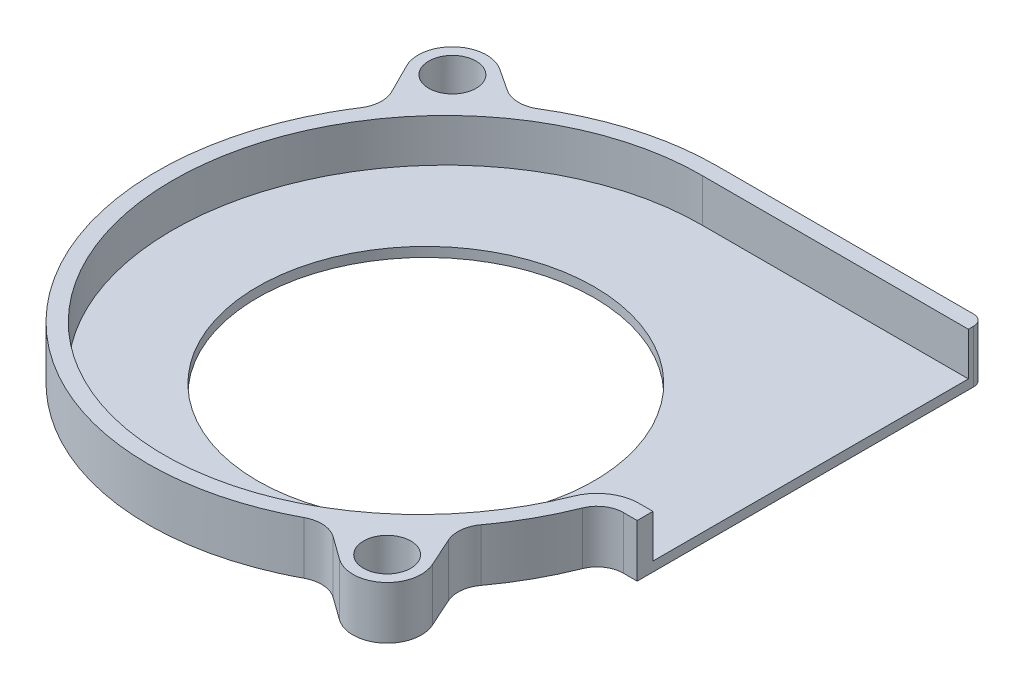
SolidWorks part; units mm, degrees
ref_plane "Front Plane" through (0, 0, 0) normal (0, 0, 1) x (1, 0, 0)
ref_plane "Top Plane" through (0, 0, 0) normal (0, 1, 0) x (1, 0, 0)
ref_plane "Right Plane" through (0, 0, 0) normal (1, 0, 0) x (0, 0, -1)
sketch "Sketch19" plane through (101.6679, 0, -9.2414) normal (0, 1, 0) x (-1, 0, 0)
  line L180 (73.5095, 9.2414) -> (95.2051, 9.2414)
  line L186 (79.9167, 11.9238) -> (79.5136, 11.896)
  line L187 (82.3906, 14.2171) -> (82.2795, 13.8418)
  line L188 (79.5136, 11.896) -> (76.2336, 11.896)
  line L189 (108.1308, 9.2414) -> (129.8264, 9.2414)
  line L190 (99.5137, 9.2414) -> (103.8222, 9.2414)
  line L191 (101.6679, 8.6855) -> (101.6679, 12.994)
  line L192 (101.6679, -18.9032) -> (101.6679, 4.3769)
  line L193 (88.3531, 30.395) -> (88.3531, 32.4937)
  line L194 (88.3531, 29.1024) -> (88.3531, 29.7557)
  line L195 (88.3531, 26.3644) -> (88.3531, 28.4631)
  line L196 (89.326, 29.4221) -> (91.4108, 29.4221)
  line L197 (88.0335, 29.4221) -> (88.6728, 29.4221)
  line L198 (85.2954, 29.4221) -> (87.3802, 29.4221)
  line L199 (117.3872, -12.6488) -> (117.3872, -10.5501)
  line L200 (117.3872, -13.9414) -> (117.3872, -13.2882)
  line L201 (117.3872, -16.6794) -> (117.3872, -14.5807)
  line L202 (118.3462, -13.6217) -> (120.4449, -13.6217)
  line L203 (117.0536, -13.6217) -> (117.7069, -13.6217)
  line L204 (114.3156, -13.6217) -> (116.4143, -13.6217)
  line L205 (100.3893, 23.6264) -> (100.3198, 24.2935)
  line L206 (98.8882, 23.4179) -> (98.7492, 24.0712)
  line L207 (97.4289, 23.0427) -> (97.2204, 23.682)
  line L208 (96.0112, 22.5284) -> (95.7333, 23.14)
  line L209 (94.6492, 21.8613) -> (94.3156, 22.445)
  line L210 (93.3705, 21.0552) -> (92.9674, 21.5972)
  line L211 (92.1752, 20.124) -> (91.7305, 20.6243)
  line L212 (91.0911, 19.0677) -> (90.5908, 19.5263)
  line L213 (90.1182, 17.9141) -> (89.5762, 18.3033)
  line L214 (89.2843, 16.6632) -> (88.7006, 16.9968)
  line L215 (88.5755, 15.329) -> (87.964, 15.593)
  line L216 (88.0057, 13.9252) -> (87.3802, 14.1337)
  line L217 (87.6026, 12.4659) -> (86.9494, 12.6049)
  line L218 (87.3385, 10.9787) -> (86.6714, 11.0482)
  line L219 (87.2412, 9.4777) -> (86.5602, 9.4777)
  line L220 (87.2968, 7.9627) -> (86.6297, 7.8932)
  line L221 (87.5053, 6.4617) -> (86.8521, 6.3227)
  line L222 (87.8667, 5.0023) -> (87.2412, 4.7939)
  line L223 (88.3948, 3.5847) -> (87.7833, 3.3067)
  line L224 (89.0619, 2.2226) -> (88.4782, 1.8891)
  line L225 (89.8542, 0.944) -> (89.3121, 0.5548)
  line L226 (90.7854, -0.2374) -> (90.2989, -0.6961)
  line L227 (91.8417, -1.3215) -> (91.3969, -1.8219)
  line L228 (93.0091, -2.2944) -> (92.6061, -2.8364)
  line L229 (94.26, -3.1422) -> (93.9264, -3.726)
  line L230 (95.5943, -3.851) -> (95.3163, -4.4626)
  line L231 (96.998, -4.407) -> (96.7895, -5.0463)
  line L232 (98.4435, -4.8239) -> (98.3045, -5.4772)
  line L233 (99.9306, -5.088) -> (99.8611, -5.7551)
  line L234 (101.4456, -5.1853) -> (101.4456, -5.8524)
  line L235 (102.9605, -5.1297) -> (103.03, -5.7968)
  line L236 (104.4476, -4.9212) -> (104.5866, -5.5745)
  line L237 (105.9209, -4.546) -> (106.1294, -5.1853)
  line L238 (107.3385, -4.0317) -> (107.6026, -4.6433)
  line L239 (108.6867, -3.3646) -> (109.0203, -3.9483)
  line L240 (109.9654, -2.5585) -> (110.3684, -3.1005)
  line L241 (111.1606, -1.6273) -> (111.6054, -2.1276)
  line L242 (112.2447, -0.571) -> (112.7451, -1.0296)
  line L243 (113.2176, 0.5826) -> (113.7597, 0.1934)
  line L244 (114.0515, 1.8335) -> (114.6353, 1.4999)
  line L245 (114.7604, 3.1677) -> (115.3719, 2.9037)
  line L246 (115.3302, 4.5715) -> (115.9696, 4.363)
  line L247 (115.7472, 6.0308) -> (116.4004, 5.8918)
  line L248 (115.9973, 7.518) -> (116.6645, 7.4485)
  line L249 (116.1085, 9.019) -> (116.7757, 9.019)
  line L250 (116.0529, 10.534) -> (116.7201, 10.6035)
  line L251 (115.8306, 12.0211) -> (116.4977, 12.174)
  line L252 (115.4692, 13.4944) -> (116.1085, 13.7028)
  line L253 (114.955, 14.912) -> (115.5665, 15.19)
  line L254 (114.2878, 16.2741) -> (114.8577, 16.6076)
  line L255 (113.4817, 17.5527) -> (114.0238, 17.9419)
  line L256 (112.5505, 18.7341) -> (113.0509, 19.1789)
  line L257 (111.4942, 19.8182) -> (111.939, 20.3185)
  line L258 (110.3406, 20.7911) -> (110.7298, 21.3331)
  line L259 (109.0759, 21.6389) -> (109.4233, 22.2088)
  line L260 (107.7416, 22.3477) -> (108.0196, 22.9593)
  line L261 (106.3517, 22.9037) -> (106.5463, 23.543)
  line L262 (104.8924, 23.3206) -> (105.0314, 23.9739)
  line L263 (103.4053, 23.5847) -> (103.4747, 24.2379)
  line L264 (101.8903, 23.682) -> (101.8903, 24.3491)
  line L265 (116.7479, 10.1587) -> (116.7757, 9.2414)
  line L266 (116.6645, 11.0621) -> (116.7479, 10.1587)
  line L267 (116.5255, 11.9655) -> (116.6645, 11.0621)
  line L268 (100.7645, 24.3213) -> (101.6679, 24.3491)
  line L269 (99.8472, 24.2379) -> (100.7645, 24.3213)
  line L270 (86.588, 10.1587) -> (86.6714, 11.0621)
  line L271 (86.5602, 9.2414) -> (86.588, 10.1587)
  line L272 (86.588, 8.338) -> (86.5602, 9.2414)
  line L273 (86.6714, 7.4207) -> (86.588, 8.338)
  line L274 (101.6679, -5.8524) -> (100.7645, -5.8246)
  line L275 (102.5852, -5.8246) -> (101.6679, -5.8524)
  line L276 (116.6645, 7.4207) -> (116.5255, 6.5312)
  line L277 (116.7479, 8.338) -> (116.6645, 7.4207)
  line L278 (116.7757, 9.2414) -> (116.7479, 8.338)
  line L279 (116.0807, 10.117) -> (116.1085, 9.2414)
  line L280 (115.9973, 10.9926) -> (116.0807, 10.117)
  line L281 (115.8723, 11.8543) -> (115.9973, 10.9926)
  line L282 (100.7923, 23.6542) -> (101.6679, 23.682)
  line L283 (99.9306, 23.5708) -> (100.7923, 23.6542)
  line L284 (87.2551, 10.117) -> (87.3385, 10.9926)
  line L285 (87.2273, 9.2414) -> (87.2551, 10.117)
  line L286 (87.2551, 8.3797) -> (87.2273, 9.2414)
  line L287 (87.3385, 7.5041) -> (87.2551, 8.3797)
  line L288 (101.6679, -5.1853) -> (100.7923, -5.1575)
  line L289 (102.5435, -5.1575) -> (101.6679, -5.1853)
  line L290 (115.9973, 7.5041) -> (115.8723, 6.6424)
  line L291 (116.0807, 8.3797) -> (115.9973, 7.5041)
  line L292 (116.1085, 9.2414) -> (116.0807, 8.3797)
  line L293 (111.9668, 9.978) -> (111.9946, 9.2414)
  line L294 (111.8834, 10.7146) -> (111.9668, 9.978)
  line L295 (111.7583, 11.4374) -> (111.8834, 10.7146)
  line L296 (100.9313, 19.5402) -> (101.6679, 19.568)
  line L297 (100.1947, 19.4707) -> (100.9313, 19.5402)
  line L298 (91.3691, 9.978) -> (91.4525, 10.7146)
  line L299 (91.3413, 9.2414) -> (91.3691, 9.978)
  line L300 (91.3691, 8.5048) -> (91.3413, 9.2414)
  line L301 (91.4525, 7.7821) -> (91.3691, 8.5048)
  line L302 (101.6679, -1.0713) -> (100.9313, -1.0435)
  line L303 (102.4046, -1.0435) -> (101.6679, -1.0713)
  line L304 (111.8834, 7.7821) -> (111.7583, 7.0593)
  line L305 (111.9668, 8.5048) -> (111.8834, 7.7821)
  line L306 (111.9946, 9.2414) -> (111.9668, 8.5048)
  line L307 (98.6797, 31.9099) -> (105.8375, 32.2852)
  line L308 (100.5838, 31.4096) -> (100.5561, 32.0211)
  line L309 (103.989, 31.6737) -> (103.9612, 32.1879)
  line L310 (105.8375, 32.2852) -> (105.8792, 31.5903)
  line L311 (98.7214, 31.0482) -> (98.6797, 31.9099)
  line L312 (86.2961, 22.8481) -> (86.9494, 23.682)
  line L313 (82.3906, 14.2171) -> (82.6269, 15.2595)
  line L314 (87.1856, 24.0156) -> (86.9494, 23.682)
  line L315 (86.7131, 27.7265) -> (86.9911, 27.4207)
  line L316 (90.6325, 30.2838) -> (90.3962, 30.6174)
  line L317 (94.2739, 29.436) -> (93.8986, 29.297)
  line L318 (90.1877, 30.9231) -> (90.3962, 30.6174)
  line L319 (86.7131, 27.7265) -> (86.4768, 27.9906)
  line L320 (90.1043, 29.7418) -> (90.1321, 29.4221)
  line L321 (90.0209, 30.0336) -> (90.1043, 29.7418)
  line L322 (86.588, 29.4221) -> (86.6158, 29.7418)
  line L323 (86.6158, 29.1163) -> (86.588, 29.4221)
  line L324 (90.1043, 29.1163) -> (90.0209, 28.8245)
  line L325 (90.1321, 29.4221) -> (90.1043, 29.1163)
  line L326 (115.2051, -14.678) -> (115.4414, -14.9699)
  line L327 (111.7166, -13.997) -> (112.0641, -13.858)
  line L328 (120.153, -7.4091) -> (119.3747, -8.2986)
  line L329 (125.6429, 4.1545) -> (125.3928, 3.0009)
  line L330 (119.1384, -8.5904) -> (119.3747, -8.2986)
  line L331 (119.2357, -12.1485) -> (119.0272, -11.8427)
  line L332 (115.6777, -15.2618) -> (115.4414, -14.9699)
  line L333 (119.2357, -12.1485) -> (119.4442, -12.4681)
  line L334 (119.1245, -13.316) -> (119.1523, -13.6217)
  line L335 (119.0411, -13.0102) -> (119.1245, -13.316)
  line L336 (115.6082, -13.6217) -> (115.636, -13.316)
  line L337 (115.636, -13.9275) -> (115.6082, -13.6217)
  line L338 (119.1245, -13.9275) -> (119.0411, -14.2194)
  line L339 (119.1523, -13.6217) -> (119.1245, -13.9275)
  line L340 (82.9466, 18.4283) -> (81.6262, 13.3137)
  line L341 (82.9883, 16.4825) -> (82.474, 16.6076)
  line L342 (82.5713, 15.0093) -> (82.0988, 15.1344)
  line L343 (81.6262, 13.3137) -> (81.9737, 13.2303)
  line L344 (83.6554, 18.2477) -> (82.9466, 18.4283)
  line L345 (126.6992, 13.411) -> (126.6992, 6.2393)
  line L346 (126.1294, 11.5347) -> (126.6992, 11.5347)
  line L347 (126.1711, 8.1156) -> (126.6992, 8.1156)
  line L348 (126.6992, 6.2393) -> (125.9904, 6.2393)
  line L349 (125.907, 13.411) -> (126.6992, 13.411)
  line L350 (90.7715, -16.5126) -> (83.5998, -16.5126)
  line L351 (88.8952, -16.0262) -> (88.8952, -16.5126)
  line L352 (85.49, -16.0262) -> (85.49, -16.5126)
  line L353 (83.5998, -16.5126) -> (83.5998, -16.0262)
  line L354 (90.7715, -16.0262) -> (90.7715, -16.5126)
  line L355 (119.7222, 25.8224) -> (120.5422, 25.0441)
  line L356 (94.2739, 29.436) -> (95.3163, 29.9086)
  line L357 (76.2336, -15.2479) -> (76.2336, 11.896)
  line L358 (76.2614, -15.4424) -> (76.2336, -15.2479)
  line L359 (76.3309, -15.637) -> (76.2614, -15.4424)
  line L360 (76.456, -15.8038) -> (76.3309, -15.637)
  line L361 (76.6227, -15.9289) -> (76.456, -15.8038)
  line L362 (76.8173, -15.9984) -> (76.6227, -15.9289)
  line L363 (77.0119, -16.0262) -> (76.8173, -15.9984)
  line L364 (103.7666, -16.0262) -> (77.0119, -16.0262)
  line L365 (104.6283, -15.9984) -> (103.7666, -16.0262)
  line L366 (105.49, -15.9289) -> (104.6283, -15.9984)
  line L367 (110.7854, -14.4278) -> (109.8264, -14.817)
  line L368 (111.7166, -13.997) -> (110.7854, -14.4278)
  line L369 (125.8514, 5.2664) -> (125.6429, 4.1545)
  line L370 (120.5422, 25.0441) -> (121.1676, 24.3908)
  spline S28 degree 3 poles (82.2795, 13.8418) (82.1213, 13.5208) (81.8076, 12.8842) (80.9543, 12.1818) (80.2645, 12.0103) (79.9167, 11.9238) knots 0 0 0 0 0.335193 0.664797 1 1 1 1
  spline S29 degree 3 poles (101.6679, 24.3491) (104.0069, 24.0252) (108.6295, 23.3848) (114.3269, 18.6424) (115.7868, 14.2088) (116.5255, 11.9655) knots 0 0 0 0 0.335972 0.664018 1 1 1 1
  spline S30 degree 3 poles (86.6714, 11.0621) (87.2366, 13.2458) (88.355, 17.5661) (93.3409, 22.5601) (97.6629, 23.6747) (99.8472, 24.2379) knots 0 0 0 0 0.335761 0.664295 1 1 1 1
  spline S31 degree 3 poles (100.7645, -5.8246) (98.4503, -5.3637) (93.8723, -4.4518) (88.48, 0.6318) (87.2787, 5.141) (86.6714, 7.4207) knots 0 0 0 0 0.335739 0.664168 1 1 1 1
  spline S32 degree 3 poles (116.5255, 6.5312) (115.8334, 4.3849) (114.4633, 0.1363) (109.1811, -4.5461) (104.7988, -5.3956) (102.5852, -5.8246) knots 0 0 0 0 0.335641 0.664413 1 1 1 1
  spline S33 degree 3 poles (101.6679, 23.682) (103.9054, 23.3721) (108.3203, 22.7605) (113.7584, 18.2278) (115.1613, 13.998) (115.8723, 11.8543) knots 0 0 0 0 0.336336 0.663662 1 1 1 1
  spline S34 degree 3 poles (87.3385, 10.9926) (87.8783, 13.0779) (88.947, 17.2069) (93.7146, 21.9749) (97.8452, 23.0354) (99.9306, 23.5708) knots 0 0 0 0 0.335633 0.664571 1 1 1 1
  spline S35 degree 3 poles (100.7923, -5.1575) (98.5828, -4.7133) (94.2132, -3.8348) (89.057, 1.0146) (87.9157, 5.3244) (87.3385, 7.5041) knots 0 0 0 0 0.335787 0.664078 1 1 1 1
  spline S36 degree 3 poles (115.8723, 6.6424) (115.2066, 4.5932) (113.8893, 0.5378) (108.8443, -3.9341) (104.6584, -4.7469) (102.5435, -5.1575) knots 0 0 0 0 0.335708 0.664385 1 1 1 1
  spline S37 degree 3 poles (101.6679, 19.568) (103.228, 19.3569) (106.3141, 18.9394) (110.1593, 15.8464) (111.2213, 12.9179) (111.7583, 11.4374) knots 0 0 0 0 0.335769 0.664184 1 1 1 1
  spline S38 degree 3 poles (91.4525, 10.7146) (91.8473, 12.1526) (92.6277, 14.9948) (95.9245, 18.2679) (98.7596, 19.0665) (100.1947, 19.4707) knots 0 0 0 0 0.335838 0.663808 1 1 1 1
  spline S39 degree 3 poles (100.9313, -1.0435) (99.3926, -0.723) (96.3435, -0.0878) (92.7284, 3.2707) (91.8804, 6.2689) (91.4525, 7.7821) knots 0 0 0 0 0.335364 0.664577 1 1 1 1
  spline S40 degree 3 poles (111.7583, 7.0593) (111.2607, 5.6562) (110.2741, 2.8742) (106.7592, -0.1744) (103.8644, -0.7521) (102.4046, -1.0435) knots 0 0 0 0 0.3353 0.664782 1 1 1 1
  spline S41 degree 3 poles (82.6269, 15.2595) (82.9027, 16.1601) (83.4547, 17.963) (84.6972, 20.5167) (85.7635, 22.0714) (86.2961, 22.8481) knots 0 0 0 0 0.333132 0.666848 1 1 1 1
  spline S42 degree 3 poles (86.9911, 27.4207) (87.1995, 27.074) (87.6163, 26.3808) (87.7039, 25.1152) (87.3583, 24.382) (87.1856, 24.0156) knots 0 0 0 0 0.333613 0.667008 1 1 1 1
  spline S43 degree 3 poles (93.8986, 29.297) (93.5019, 29.2146) (92.707, 29.0495) (91.4909, 29.4223) (90.9183, 29.9969) (90.6325, 30.2838) knots 0 0 0 0 0.332897 0.666933 1 1 1 1
  spline S44 degree 3 poles (86.4768, 27.9906) (86.1885, 28.8219) (85.6369, 30.4125) (88.0271, 32.3046) (89.4462, 31.3972) (90.1877, 30.9231) knots 0 0 0 0 0.343302 0.656868 1 1 1 1
  spline S45 degree 3 poles (86.6158, 29.7418) (86.8446, 30.2312) (87.2875, 31.1785) (89.1095, 31.3307) (89.7103, 30.4757) (90.0209, 30.0336) knots 0 0 0 0 0.340481 0.658978 1 1 1 1
  spline S46 degree 3 poles (90.0209, 28.8245) (89.7109, 28.3825) (89.1105, 27.5268) (87.2866, 27.6775) (86.8442, 28.6264) (86.6158, 29.1163) knots 0 0 0 0 0.340673 0.659593 1 1 1 1
  spline S47 degree 3 poles (112.0641, -13.858) (112.441, -13.7794) (113.1871, -13.6238) (114.3407, -13.9227) (114.915, -14.4245) (115.2051, -14.678) knots 0 0 0 0 0.335636 0.664286 1 1 1 1
  spline S48 degree 3 poles (125.3928, 3.0009) (125.0296, 1.749) (124.3006, -0.7644) (122.5332, -4.2934) (120.9444, -6.3732) (120.153, -7.4091) knots 0 0 0 0 0.332521 0.667547 1 1 1 1
  spline S49 degree 3 poles (119.0272, -11.8427) (118.8653, -11.4887) (118.5486, -10.7962) (118.5971, -9.6046) (118.9553, -8.9336) (119.1384, -8.5904) knots 0 0 0 0 0.338158 0.661533 1 1 1 1
  spline S50 degree 3 poles (119.4442, -12.4681) (119.6189, -13.254) (119.9552, -14.7658) (117.7357, -16.4106) (116.3823, -15.6551) (115.6777, -15.2618) knots 0 0 0 0 0.341627 0.657242 1 1 1 1
  spline S51 degree 3 poles (115.636, -13.316) (115.865, -12.8234) (116.3062, -11.8746) (118.1297, -11.7064) (118.7298, -12.5648) (119.0411, -13.0102) knots 0 0 0 0 0.341897 0.65855 1 1 1 1
  spline S52 degree 3 poles (119.0411, -14.2194) (118.7323, -14.663) (118.1357, -15.52) (116.3165, -15.3612) (115.8684, -14.4173) (115.636, -13.9275) knots 0 0 0 0 0.340624 0.657859 1 1 1 1
  spline S53 degree 3 poles (95.3163, 29.9086) (98.1066, 30.7198) (103.6867, 32.3422) (112.6245, 30.9005) (117.3564, 27.515) (119.7222, 25.8224) knots 0 0 0 0 0.333391 0.66672 1 1 1 1
  spline S54 degree 3 poles (109.8264, -14.817) (109.3624, -14.9921) (108.4256, -15.3457) (106.9748, -15.7324) (105.9817, -15.8638) (105.49, -15.9289) knots 0 0 0 0 0.331237 0.668901 1 1 1 1
  spline S55 degree 3 poles (121.1676, 24.3908) (122.4335, 22.5329) (124.9882, 18.7834) (126.4142, 12.0045) (126.0381, 7.5014) (125.8514, 5.2664) knots 0 0 0 0 0.330973 0.667942 1 1 1 1
sketch "Sketch18" plane through (0, 0, 0) normal (0, 1, 0) x (1, 0, 0)
  line L0 (-23.0057, 21.1739) -> (-21.5825, 18.3332)
  line L1 (14.4232, -22.6366) -> (12.2821, -21.0936)
  line L2 (-18.3115, 25.3434) -> (-16.2051, 23.9551)
  line L3 (-16.9421, 19.0744) -> (0, 0) construction
  line L4 (16.3234, -20) -> (0, 0) construction
  line L5 (-33.0815, -23.9) -> (4.114, -23.9) construction
  line L6 (-26.2, -10.7544) -> (-26.2, -0.8211) construction
  line L7 (0, 0) -> (0, -6.8242) construction
  line L8 (-4, 0) -> (-4, -27.6209) construction
  line L9 (4, 0) -> (4, -27.6209) construction
  line L10 (0, 0) -> (0, 25.466) construction
  line L11 (0.75, 0) -> (0.75, 25.466) construction
  line L12 (-0.75, 0) -> (-0.75, 25.466) construction
  line L13 (-12.8119, -19.8447) -> (10.3119, 23.6447) construction
  line L14 (-21.6522, 12.748) -> (19.1522, -8.948) construction
  line L15 (-1.25, 1.9) -> (3.3669, 1.9) construction
  line L16 (0, 0) -> (21.8429, 12.611) construction
  line L17 (0, 0) -> (-26.1434, 15.0939) construction
  line L18 (0, 0) -> (-23.531, -13.5856) construction
  line L19 (-0.0106, 27.7) -> (24.4, 27.7)
  line L20 (0, 0) -> (22.2135, -12.825) construction
  line L21 (0, 0) -> (6.1332, 0) construction
  line L22 (4, 0) -> (4, -6.8242) construction
  line L23 (-4, 0) -> (-4, -6.8242) construction
  line L24 (-1.5, 0) -> (-26.5184, 14.4444) construction
  line L25 (-1.5, 0) -> (-23.906, -12.9361) construction
  line L26 (25.4, 26.7) -> (25.4, -5.3)
  line L27 (25.4, -5.3) -> (22.3333, -5.3)
  line L28 (1.5, 0) -> (-25.7684, 15.7434) construction
  line L29 (1.5, 0) -> (-23.156, -14.2351) construction
  line L30 (9.3582, -4.5369) -> (22.5885, -12.1755) construction
  line L31 (19.2873, -18.6667) -> (18.0311, -15.874)
  line L157 (8.6082, -5.836) -> (21.8385, -13.4745) construction
  line L159 (9.3582, 4.5369) -> (22.2179, 11.9615) construction
  line L161 (8.6082, 5.836) -> (21.4679, 13.2605) construction
  line L164 (11.0633, 27.6622) -> (11.0633, 28.1486) construction
  line L165 (18.2349, 28.1486) -> (18.2349, 27.6622) construction
  line L166 (16.3586, 27.6622) -> (16.3586, 28.1486) construction
  line L167 (12.9535, 27.6622) -> (12.9535, 28.1486) construction
  line L168 (11.0633, 28.1486) -> (18.2349, 28.1486) construction
  line L169 (-26.0052, -3.975) -> (-26.3506, -3.975) construction
  line L170 (-26.3506, 3.1828) -> (-25.7716, 3.1828) construction
  line L171 (-26.1178, 1.3065) -> (-26.3506, 1.3065) construction
  line L172 (-26.0193, -2.0987) -> (-26.3506, -2.0987) construction
  line L173 (-26.3506, -3.975) -> (-26.3506, 3.1828) construction
  line L174 (19.9063, -12.0569) -> (20.36, -12.2293) construction
  line L175 (22.6116, -6.1418) -> (22.2945, -6.0236) construction
  line L176 (21.4807, -7.7289) -> (21.9583, -7.9069) construction
  line L177 (20.6345, -10.3321) -> (21.0132, -10.4642) construction
  line L178 (20.36, -12.2293) -> (22.6116, -6.1418) construction
  circle A0 centre (16.3234, -20) radius 2.25
  arc A1 (19.2873, -18.6667) -> (14.4232, -22.6366) centre (16.3234, -20) ccw construction
  circle A2 centre (-20.1, 22.6298) radius 2.25
  arc A3 (-18.3115, 25.3434) -> (-23.0057, 21.1739) centre (-20.1, 22.6298) ccw
  circle A4 centre (0, 0) radius 9.2 construction
  arc A5 (-16.2051, 23.9551) -> (-13.1979, 23.9077) centre (-14.6643, 26.293) ccw
  arc A6 (-21.5825, 18.3332) -> (-21.7386, 15.5524) centre (-24.0858, 17.079) cw
  arc A7 (-23.0057, 21.1739) -> (-18.3115, 25.3434) centre (-20.1, 22.6298) ccw construction
  arc A8 (12.2821, -21.0936) -> (9.3249, -20.8959) centre (10.6451, -23.3651) ccw
  arc A9 (25.4, 26.7) -> (24.4, 27.7) centre (24.4, 26.7) ccw
  circle A10 centre (0, 0) radius 10.4 construction
  arc A11 (18.0311, -15.874) -> (18.3294, -13.0658) centre (20.5846, -14.7253) cw
  arc A12 (14.4232, -22.6366) -> (19.2873, -18.6667) centre (16.3234, -20) ccw
  circle A13 centre (0, 0) radius 16
  ellipse E0 centre (-1.25, 1.9) end of major axis (10.3119, 23.6447) minor radius 23.1069 construction
  ellipse E1 centre (-1.25, 1.9) end of major axis (-13.5161, -21.1691) minor radius 24.6069 (-21.7386, 15.5524) -> (9.3249, -20.8959) ccw
  ellipse E2 centre (-1.25, 1.9) end of major axis (-13.5161, -21.1691) minor radius 24.6069 (-0.0106, 27.7) -> (-13.1979, 23.9077) ccw
  ellipse E3 centre (-1.25, 1.9) end of major axis (-13.5161, -21.1691) minor radius 24.6069 (22.3333, -5.3) -> (-0.0106, 27.7) ccw construction
  ellipse E4 centre (-1.25, 1.9) end of major axis (-13.5161, -21.1691) minor radius 24.6069 (18.3294, -13.0658) -> (22.3333, -5.3) ccw
  dimension "D1" = 6.5
  dimension "D2" = 4.5
  dimension "D4" = 32
  dimension "D5" = 2.8
  dimension "D7" = 0.75
  dimension "D8" = 1
  dimension "D16" = 18.4
  dimension "D34" = 15
  dimension "D6" = 15
  dimension "D9" = 16.3234
  dimension "D10" = 20.1
  dimension "D11" = 25.4
  dimension "D12" = 27.7
  dimension "D13" = 51.6
  dimension "D14" = 20
  dimension "D15" = 51.6
  dimension "D21" = 32
  dimension "D22" = 28
  dimension "D23" = 0.75
  dimension "D24" = 1.9
  dimension "D25" = 1.25
  dimension "D26" = 1.5
  dimension "D27" = 1.5
  dimension "D28" = 30
  dimension "D29" = 30
  dimension "D30" = 30
  dimension "D31" = 30
  dimension "D33" = 48.388
  dimension "D17" = 4
  dimension "D18" = 4
  dimension "D19" = 1.2
  dimension "D20" = 0.75
  dimension "D32" = 0.75
extrude "Boss-Extrude2" add sketch "Sketch18" along normal blind 0.91
fillet "Fillet1" radius 2.5 1 edges at (22.3333, 0.455, 5.3)
sketch "Sketch22" plane through (0, 0.91, 0) normal (0, -1, 0) x (-1, 0, 0)
  line L0 (0.0106, 27.7) -> (-24.4, 27.7) construction
  line L1 (-25.4, 26.7) -> (-25.4, -5.3) construction
  line L2 (-25.4, -5.3) -> (-22.3333, -5.3) construction
  line L3 (-19.2873, -18.6667) -> (-18.0311, -15.874) construction
  line L4 (-22.3333, -5.3) -> (-18.3294, -13.0658) construction
  line L5 (-21.419, -3.8) -> (-17.0448, -12.284) construction
  line L6 (13.1979, 23.9077) -> (0.0106, 27.7) construction
  line L7 (12.608, 22.5165) -> (-0.2008, 26.2) construction
  line L8 (-9.3249, -20.8959) -> (21.7386, 15.5524) construction
  line L9 (-9.8059, -19.1478) -> (19.98, 15.8015) construction
  line L10 (-25.4, -5.3) -> (-22.3333, -5.3) construction
  line L13 (-14.4232, -22.6366) -> (-12.2821, -21.0936) construction
  line L14 (23.0057, 21.1739) -> (21.5825, 18.3332) construction
  line L15 (18.3115, 25.3434) -> (16.2051, 23.9551) construction
  line L16 (0.0106, 27.7) -> (-24.4, 27.7)
  line L17 (-25.4, 26.7) -> (-25.4, 26.2)
  line L18 (-25.4, -5.3) -> (-24.0846, -5.3)
  line L20 (-19.2873, -18.6667) -> (-18.0311, -15.874)
  line L21 (-14.4232, -22.6366) -> (-12.2821, -21.0936)
  line L22 (23.0057, 21.1739) -> (21.5825, 18.3332)
  line L23 (18.3115, 25.3434) -> (16.2051, 23.9551)
  line L24 (-25.4, -3.8) -> (-25.4, -5.3)
  line L25 (-25.4, -3.8) -> (-24.0847, -3.8)
  line L30 (-0.1345, 26.2) -> (-25.4, 26.2)
  line L31 (-0.2008, 26.2) -> (-23.9, 26.2) construction
  line L32 (-23.9, 26.2) -> (-23.9, -3.8) construction
  line L33 (-23.9, -3.8) -> (-21.419, -3.8) construction
  line L34 (-25.4, 26.7) -> (-25.4, -5.3) construction
  line L35 (19.137, 24.0909) -> (17.0306, 22.7027) construction
  line L36 (21.6646, 21.8459) -> (20.2414, 19.0052) construction
  line L37 (-17.9194, -19.2821) -> (-16.6631, -16.4894) construction
  line L38 (-15.3002, -21.4197) -> (-13.1592, -19.8767) construction
  arc A0 (-21.7614, -6.8766) -> (-24.0846, -5.3) centre (-24.0846, -7.8) ccw construction
  arc A1 (-21.7614, -6.8766) -> (-24.0846, -5.3) centre (-24.0846, -7.8) ccw
  arc A2 (-24.4, 27.7) -> (-25.4, 26.7) centre (-24.4, 26.7) ccw construction
  arc A3 (-18.0311, -15.874) -> (-18.3294, -13.0658) centre (-20.5846, -14.7253) ccw construction
  arc A4 (-19.2873, -18.6667) -> (-14.4232, -22.6366) centre (-16.3234, -20) ccw construction
  arc A5 (-9.3249, -20.8959) -> (-12.2821, -21.0936) centre (-10.6451, -23.3651) ccw construction
  arc A6 (-20.3675, -6.3226) -> (-24.0847, -3.8) centre (-24.0847, -7.8) ccw
  arc A15 (21.5825, 18.3332) -> (21.7386, 15.5524) centre (24.0858, 17.079) ccw construction
  arc A16 (23.0057, 21.1739) -> (18.3115, 25.3434) centre (20.1, 22.6298) ccw construction
  arc A17 (13.1979, 23.9077) -> (16.2051, 23.9551) centre (14.6643, 26.293) ccw construction
  arc A18 (-24.4, 27.7) -> (-25.4, 26.7) centre (-24.4, 26.7) ccw
  arc A19 (-18.0311, -15.874) -> (-18.3294, -13.0658) centre (-20.5846, -14.7253) ccw
  arc A20 (-19.2873, -18.6667) -> (-14.4232, -22.6366) centre (-16.3234, -20) ccw
  arc A21 (-9.3249, -20.8959) -> (-12.2821, -21.0936) centre (-10.6451, -23.3651) ccw
  arc A22 (21.5825, 18.3332) -> (21.7386, 15.5524) centre (24.0858, 17.079) ccw
  arc A23 (23.0057, 21.1739) -> (18.3115, 25.3434) centre (20.1, 22.6298) ccw
  arc A24 (13.1979, 23.9077) -> (16.2051, 23.9551) centre (14.6643, 26.293) ccw
  circle A25 centre (20.1, 22.6298) radius 2.25 construction
  arc A32 (-23.9, 26.2) -> (-23.9, 26.2) centre (-23.9, 26.2) ccw construction
  circle A33 centre (20.1, 22.6298) radius 2.25
  circle A34 centre (-16.3234, -20) radius 2.25 construction
  circle A35 centre (-16.3234, -20) radius 2.25
  arc A36 (21.6646, 21.8459) -> (19.137, 24.0909) centre (20.1, 22.6298) ccw construction
  arc A37 (12.608, 22.5165) -> (17.0306, 22.7027) centre (14.6643, 26.293) ccw construction
  arc A38 (20.2414, 19.0052) -> (19.98, 15.8015) centre (24.0858, 17.079) ccw construction
  arc A39 (-16.6631, -16.4894) -> (-17.0448, -12.284) centre (-20.5846, -14.7253) ccw construction
  arc A40 (-17.9194, -19.2821) -> (-15.3002, -21.4197) centre (-16.3234, -20) ccw construction
  arc A41 (-9.8059, -19.1478) -> (-13.1592, -19.8767) centre (-10.6451, -23.3651) ccw construction
  ellipse E0 centre (1.25, 1.9) end of major axis (-10.3119, 23.6447) minor radius 23.1069 (-20.3675, -6.3226) -> (-0.1345, 26.2) ccw
  ellipse E1 centre (1.25, 1.9) end of major axis (13.5161, -21.1691) minor radius 24.6069 (-22.3333, -5.3) -> (-18.3294, -13.0658) ccw construction
  ellipse E5 centre (1.25, 1.9) end of major axis (13.5161, -21.1691) minor radius 24.6069 (-9.3249, -20.8959) -> (21.7386, 15.5524) ccw construction
  ellipse E6 centre (1.25, 1.9) end of major axis (13.5161, -21.1691) minor radius 24.6069 (13.1979, 23.9077) -> (0.0106, 27.7) ccw construction
  ellipse E7 centre (1.25, 1.9) end of major axis (13.5161, -21.1691) minor radius 24.6069 (-21.7614, -6.8766) -> (-18.3294, -13.0658) ccw
  ellipse E8 centre (1.25, 1.9) end of major axis (13.5161, -21.1691) minor radius 24.6069 (-9.3249, -20.8959) -> (21.7386, 15.5524) ccw
  ellipse E9 centre (1.25, 1.9) end of major axis (13.5161, -21.1691) minor radius 24.6069 (13.1979, 23.9077) -> (0.0106, 27.7) ccw
  dimension "D2" = 4
  dimension "D1" = 1.5
extrude "Boss-Extrude3" add sketch "Sketch22" against normal blind 4.09
